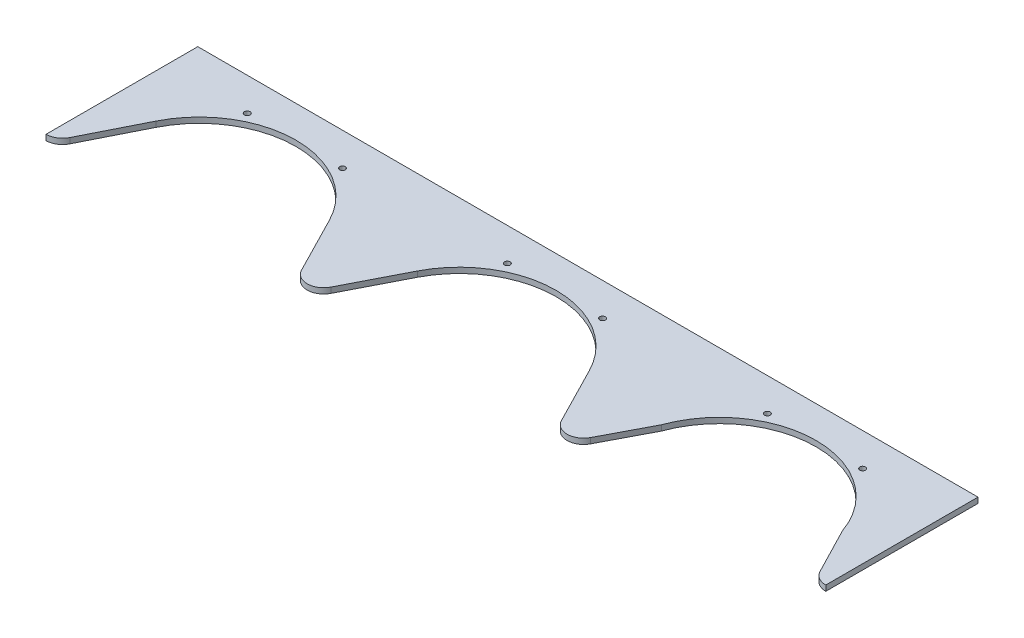
SolidWorks part; units mm, degrees
ref_plane "Front Plane" through (0, 0, 0) normal (0, 0, 1) x (1, 0, 0)
ref_plane "Top Plane" through (0, 0, 0) normal (0, 1, 0) x (1, 0, 0)
ref_plane "Right Plane" through (0, 0, 0) normal (1, 0, 0) x (0, 0, -1)
sketch "Sketch1" plane through (0, 0, 0) normal (0, 1, 0) x (1, 0, 0)
  line L0 (-129.7899, -67.5734) -> (-129.7899, 62.6016)
  line L1 (-280.0732, 62.6016) -> (170.7768, 62.6016)
  line L2 (-280.0732, 62.6016) -> (-280.0732, -25.1078)
  line L3 (-280.0732, -67.5734) -> (177.1268, -67.5734)
  line L4 (170.7768, 62.6016) -> (170.7768, -25.3728)
  line L5 (20.4934, -67.5734) -> (20.4934, 62.6016)
  line L6 (-155.1955, 13.7801) -> (-129.7899, -35.8234)
  line L7 (-129.7899, -35.8234) -> (-104.3843, 13.7801)
  line L8 (-4.9122, 13.7801) -> (20.4934, -35.8234)
  line L9 (20.4934, -35.8234) -> (50.0821, 20.6717)
  line L10 (-254.8688, 13.3835) -> (-271.5612, -19.8573)
  line L11 (141.188, 20.6717) -> (162.3144, -20.2198)
  circle A0 centre (-204.9316, -11.6934) radius 55.88
  circle A1 centre (-54.6482, -11.6934) radius 55.88
  circle A2 centre (95.6351, -11.6934) radius 55.88
  circle A3 centre (-280.0732, -15.5828) radius 9.525
  circle A4 centre (170.7768, -15.8478) radius 9.525
  circle A9 centre (-232.4398, 43.5516) radius 1.6383
  circle A10 centre (-177.4234, 43.5516) radius 1.6383
  circle A11 centre (-82.1564, 43.5516) radius 1.6383
  circle A12 centre (-27.14, 43.5516) radius 1.6383
  circle A13 centre (68.1269, 43.5516) radius 1.6383
  circle A14 centre (123.1433, 43.5516) radius 1.6383
  dimension "D3" = 111.76
  dimension "D4" = 111.76
  dimension "D5" = 111.76
  dimension "D15" = 3.2766
  dimension "D16" = 3.2766
  dimension "D17" = 3.2766
  dimension "D18" = 3.2766
  dimension "D19" = 3.2766
  dimension "D20" = 3.2766
  dimension "D24" = 19.05
  dimension "D25" = 19.05
  dimension "D1" = 450.85
  dimension "D2" = 130.175
  dimension "D6" = 150.2833
  dimension "D7" = 150.2833
  dimension "D8" = 75.1417
  dimension "D9" = 75.1417
  dimension "D10" = 75.1417
  dimension "D11" = 55.0164
  dimension "D12" = 27.5082
  dimension "D13" = 55.0164
  dimension "D14" = 27.5082
  dimension "D21" = 19.05
  dimension "D22" = 55.0164
  dimension "D23" = 27.5082
  dimension "D29" = 31.75
  dimension "D30" = 31.75
extrude "Boss-Extrude1" add sketch "Sketch1" against normal blind 3.175 contours A3 L10 A0 L6 L0 L1 L2 A10 A9 | L2 A3 | A1 L8 L5 L1 L0 L7 A12 A11 | A4 L4 L1 L5 L9 A2 L11 A14 A13 | L4 A4
fillet "Fillet3" radius 9.525 2 edges at (20.4934, -1.5875, 35.8234) (-129.7899, -1.5875, 35.8234)
